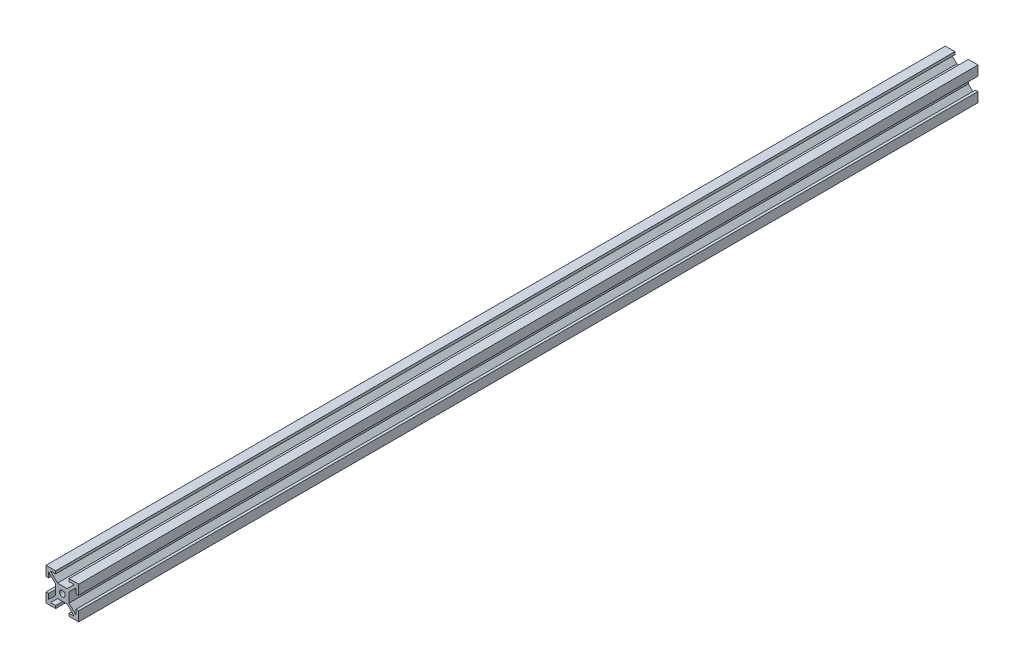
SolidWorks part; units mm, degrees
ref_plane "Front Plane" through (0, 0, 0) normal (0, 0, 1) x (1, 0, 0)
ref_plane "Top Plane" through (0, 0, 0) normal (0, 1, 0) x (1, 0, 0)
ref_plane "Right Plane" through (0, 0, 0) normal (1, 0, 0) x (0, 0, -1)
sketch "Sketch1" plane through (0, 0, 0) normal (0, 0, 1) x (1, 0, 0)
  line L0 (-8.38, 4.1) -> (-10, 4.1)
  line L1 (-2.9545, 4.1) -> (2.9545, 4.1)
  line L2 (-4.1, 2.9545) -> (-4.1, -2.9545)
  line L3 (-2.9545, -4.1) -> (2.9545, -4.1)
  line L4 (4.1, 2.9545) -> (4.1, -2.9545)
  line L5 (-4.1, 4.1) -> (4.1, -4.1) construction
  line L6 (-4.1, -4.1) -> (4.1, 4.1) construction
  line L7 (-10, 10) -> (-4.1, 10)
  line L8 (-10, 10) -> (-10, 4.1)
  line L9 (-10, -10) -> (-4.1, -10)
  line L10 (10, 10) -> (10, 4.1)
  line L11 (-10, 10) -> (10, -10) construction
  line L12 (-10, -10) -> (10, 10) construction
  line L13 (-7.2345, 8.38) -> (-4.1, 8.38)
  line L14 (-8.38, 7.2345) -> (-8.38, 4.1)
  line L15 (-7.2345, -8.38) -> (-4.1, -8.38)
  line L16 (8.38, 7.2345) -> (8.38, 4.1)
  line L17 (-8.38, 8.38) -> (8.38, -8.38) construction
  line L18 (-8.38, -8.38) -> (8.38, 8.38) construction
  line L19 (-4.1, 8.38) -> (-4.1, 10)
  line L20 (4.1, 10) -> (4.1, 8.38)
  line L21 (8.38, 4.1) -> (10, 4.1)
  line L22 (-8.38, -4.1) -> (-10, -4.1)
  line L23 (-4.1, -8.38) -> (-4.1, -10)
  line L24 (8.38, -4.1) -> (10, -4.1)
  line L25 (4.1, -8.38) -> (4.1, -10)
  line L26 (-5.464, 5.464) -> (-4.8912, 6.0368) construction
  line L27 (-4.1, 2.9545) -> (-8.38, 7.2345)
  line L28 (-2.9545, 4.1) -> (-7.2345, 8.38)
  line L29 (0, 11.3108) -> (0, -17.1823) construction
  line L30 (-16.7028, 0) -> (14.4032, 0) construction
  line L31 (-2.9545, -4.1) -> (-7.2345, -8.38)
  line L32 (-4.1, -2.9545) -> (-8.38, -7.2345)
  line L33 (2.9545, -4.1) -> (7.2345, -8.38)
  line L34 (4.1, -2.9545) -> (8.38, -7.2345)
  line L35 (4.1, 2.9545) -> (8.38, 7.2345)
  line L36 (2.9545, 4.1) -> (7.2345, 8.38)
  line L37 (4.1, 8.38) -> (7.2345, 8.38)
  line L38 (4.1, 10) -> (10, 10)
  line L39 (-8.38, -4.1) -> (-8.38, -7.2345)
  line L40 (-10, -4.1) -> (-10, -10)
  line L41 (8.38, -4.1) -> (8.38, -7.2345)
  line L42 (10, -4.1) -> (10, -10)
  line L43 (4.1, -8.38) -> (7.2345, -8.38)
  line L44 (4.1, -10) -> (10, -10)
  circle A0 centre (0, 0) radius 1.77
  point P0 (0, 0)
  point P6 (0, 0)
  dimension "D5" = 3.54
  dimension "D1" = 8.2
  dimension "D2" = 20
  dimension "D3" = 8.2
  dimension "D4" = 20
  dimension "D6" = 16.76
  dimension "D7" = 16.76
  dimension "D8" = 0.81
  dimension "D9" = 135
  dimension "D10" = 7.7696
  dimension "D11" = 5.0536
extrude "Boss-Extrude1" add sketch "Sketch1" along normal blind 550
